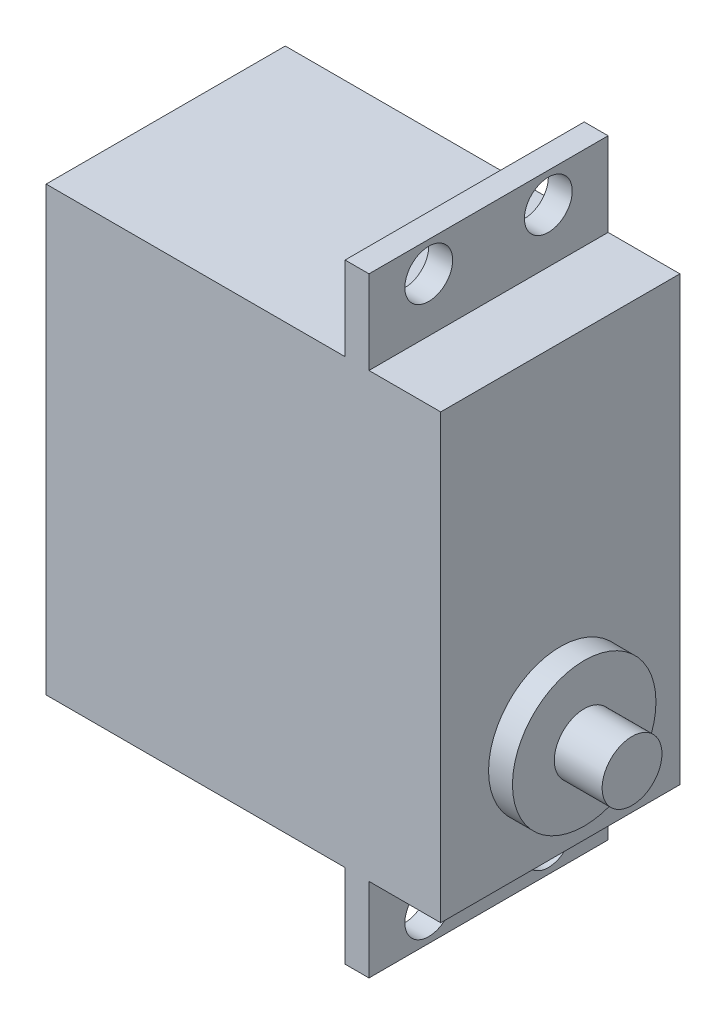
SolidWorks part; units mm, degrees
ref_plane "Plan de face" through (0, 0, 0) normal (0, 0, 1) x (1, 0, 0)
ref_plane "Plan de dessus" through (0, 0, 0) normal (0, 1, 0) x (1, 0, 0)
ref_plane "Plan de droite" through (0, 0, 0) normal (1, 0, 0) x (0, 0, -1)
sketch "Esquisse2" plane through (0, 0, 0) normal (0, 1, 0) x (1, 0, 0)
  line L1 (0, 0) -> (33, 0)
  line L2 (0, 0) -> (0, 20)
  line L3 (0, 20) -> (33, 20)
  line L4 (33, 0) -> (33, 20)
  dimension "D1" = 20
  dimension "D2" = 33
extrude "Boss.-Extru.1" add sketch "Esquisse2" along normal blind 18.5
sketch "Esquisse3" plane through (0, 0, 0) normal (0, -1, 0) x (1, 0, 0)
  line L0 (0, 0) -> (33, 0) construction
  line L1 (25, 0) -> (27, 0)
  line L2 (25, 0) -> (25, -20)
  line L3 (25, -20) -> (27, -20)
  line L4 (27, 0) -> (27, -20)
  line L5 (33, -20) -> (0, -20) construction
  dimension "D1" = 25
  dimension "D2" = 2
extrude "Boss.-Extru.2" add sketch "Esquisse3" along normal blind 7
mirror "Symétrie1" about plane through (0, 18.5, 0) normal (0, -1, 0) of "Boss.-Extru.1", "Boss.-Extru.2"
sketch "Esquisse4" plane through (33, 0, 0) normal (1, 0, 0) x (0, 0, -1)
  line L1 (20, 37) -> (20, 0) construction
  line L3 (0, 0) -> (20, 0) construction
  circle A0 centre (10, 9) radius 6
  dimension "D2" = 12
  dimension "D1" = 10
  dimension "D3" = 9
extrude "Boss.-Extru.3" add sketch "Esquisse4" along normal blind 2
sketch "Esquisse5" plane through (35, 0, 0) normal (1, 0, 0) x (0, 0, -1)
  circle A0 centre (10, 9) radius 2.5
  circle A1 centre (10, 9) radius 6 construction
  dimension "D1" = 5
extrude "Boss.-Extru.4" add sketch "Esquisse5" along normal blind 4
hole_wizard "Diamètre du perçage Ø4.0 (4)1" positions "Esquisse8" profile "Esquisse9" hole size "Ø4.0" standard "Ansi Metric" end condition up to next
sketch "Esquisse8" plane through (27, 0, 0) normal (1, 0, 0) x (0, 0, -1)
  line L0 (20, 44) -> (20, 37) construction
  line L2 (20, 37) -> (0, 37) construction
  line L3 (0, 44) -> (0, 37) construction
  line L4 (20, -7) -> (20, 0) construction
  line L5 (20, 0) -> (0, 0) construction
  line L6 (0, -7) -> (0, 0) construction
  line L7 (0, 0) -> (20, 0) construction
  point P0 (15, 41.5)
  point P2 (5, 41.5)
  point P16 (15, -4.5)
  point P18 (5, -4.5)
  dimension "D1" = 5
  dimension "D2" = 4.5
  dimension "D3" = 5
  dimension "D4" = 5
  dimension "D5" = 4.5
  dimension "D6" = 5
  dimension "D7" = 4.5
sketch "Esquisse9" plane through (27, 41.5, -15) normal (0, 1, 0) x (0, 0, -1)
  line L0 (0, 0) -> (0, 2)
  line L1 (0, 2) -> (2, 2)
  line L2 (2, 2) -> (2, 0)
  line L5 (2, 0) -> (0, 0)
  line L11 (0, -6.35) -> (0, 107.95) construction
  dimension "Diamètre du perçage jusqu'au prochain" = 4
  dimension "Profondeur du perçage jusqu'au prochain" = 2
